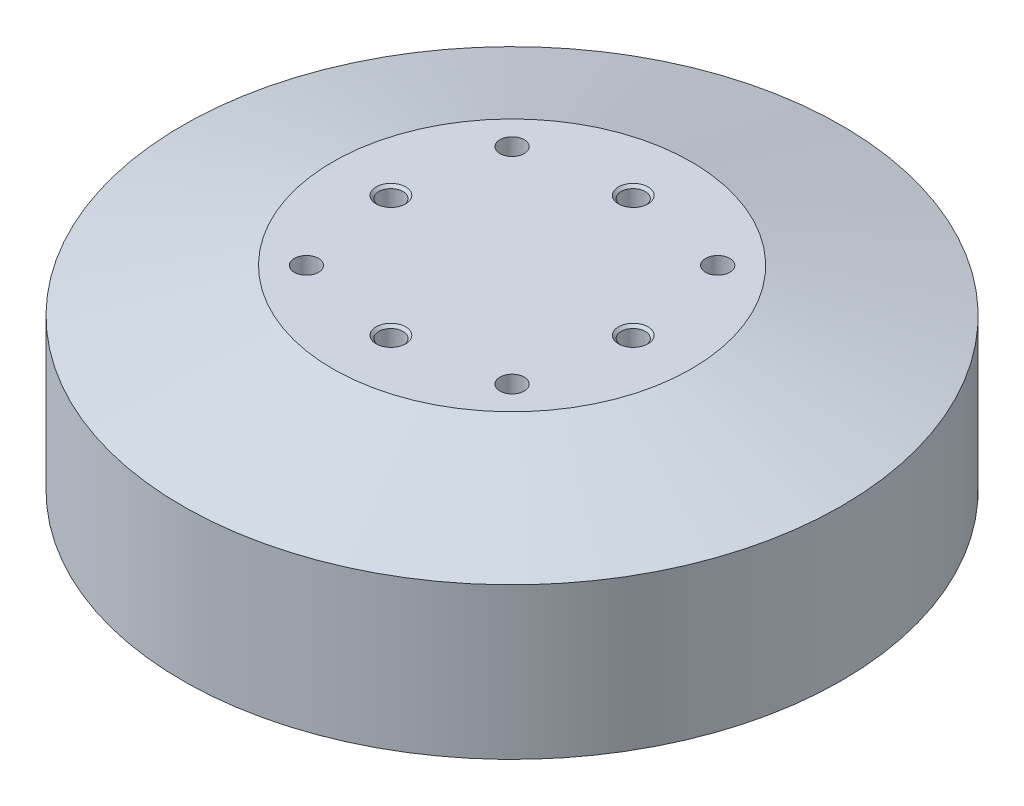
SolidWorks part; units mm, degrees
ref_plane "Front" through (0, 0, 0) normal (0, 0, 1) x (1, 0, 0)
ref_plane "Top" through (0, 0, 0) normal (0, 1, 0) x (1, 0, 0)
ref_plane "Right" through (0, 0, 0) normal (1, 0, 0) x (0, 0, -1)
sketch "Sketch3" plane through (0, 0, 0) normal (0, 0, 1) x (1, 0, 0)
  line L0 (0, -10.05) -> (0, 10.05)
  line L1 (0, 10.05) -> (18.5, 10.05)
  line L2 (18.5, 10.05) -> (34, 5.55)
  line L3 (34, 5.55) -> (34, -10.05)
  line L4 (34, -10.05) -> (0, -10.05)
  point P4 (0, 0)
  dimension "D1" = 18.5
  dimension "D2" = 4.5
  dimension "D3" = 34
  dimension "D4" = 20.1
revolve "Revolve1" add sketch "Sketch3" angle 360 about L0
sketch "Sketch4" plane through (0, -10.05, 0) normal (0, -1, 0) x (1, 0, 0)
  circle A0 centre (0, 0) radius 33
  circle A1 centre (0, 0) radius 34 construction
  dimension "D1" = 1
extrude "Cut-Extrude1" cut sketch "Sketch4" against normal blind 2
sketch "Sketch6" plane through (0, 10.05, 0) normal (0, 1, 0) x (1, 0, 0)
  line L0 (-10.6066, -10.6066) -> (10.6066, 10.6066) construction
  line L5 (10.6066, -10.6066) -> (-10.6066, 10.6066) construction
  line L6 (0, 0) -> (0, 15) construction
  circle A0 centre (0, 0) radius 15 construction
  point P4 (0, 0)
  point P9 (0, 0)
  dimension "D1" = 30
  dimension "D2" = 45
hole_wizard "M3x0.5 Tapped Hole1" positions "Sketch7" profile "Sketch8" tap size "M3x0.5" standard "ANSI Metric"
sketch "Sketch7" plane through (0, 10.05, 0) normal (0, 1, 0) x (1, 0, 0)
  point P0 (-10.6066, 10.6066)
  point P3 (10.6066, 10.6066)
  point P6 (10.6066, -10.6066)
  point P9 (-10.6066, -10.6066)
sketch "Sketch8" plane through (-10.6066, 10.05, -10.6066) normal (1, 0, 0) x (0, 0, 1)
  line L0 (0, 0) -> (0, 8.2511)
  line L1 (0, 8.2511) -> (1.25, 7.5)
  line L2 (1.25, 7.5) -> (1.25, 0)
  line L5 (1.25, 0) -> (0, 0)
  line L10 (0, 8.2511) -> (-1.25, 7.5) construction
  line L11 (0, -6.35) -> (0, 107.95) construction
  dimension "Tap Drill Dia." = 2.5
  dimension "Tap Drill Depth" = 7.5
  dimension "Drill Angle" = 118
cosmetic thread "Hole Thread1" parameters "D1"=6, "D2"=3
cosmetic thread "Hole Thread2" parameters "D1"=6, "D2"=3
cosmetic thread "Hole Thread3" parameters "D1"=6, "D2"=3
cosmetic thread "Hole Thread4" parameters "D1"=6, "D2"=3
sketch "Sketch9" plane through (0, 10.05, 0) normal (0, 1, 0) x (1, 0, 0)
  circle A0 centre (0, 0) radius 12.5 construction
  point P3 (0, 12.5)
  point P4 (0, -12.5)
  point P5 (12.5, 0)
  point P6 (-12.5, 0)
  dimension "D1" = 25
hole_wizard "M3x0.5 Tapped Hole2" positions "Sketch10" profile "Sketch11" tap size "M3x0.5" standard "ANSI Metric"
sketch "Sketch10" plane through (0, 10.05, 0) normal (0, 1, 0) x (1, 0, 0)
  point P0 (0, 12.5)
  point P3 (0, -12.5)
  point P6 (-12.5, 0)
  point P9 (12.5, 0)
sketch "Sketch11" plane through (0, 10.05, -12.5) normal (1, 0, 0) x (0, 0, 1)
  line L0 (0, 0) -> (0, 8.2511)
  line L1 (0, 8.2511) -> (1.25, 7.5)
  line L2 (1.25, 7.5) -> (1.25, 0.275)
  line L3 (1.25, 0.275) -> (1.525, 0)
  line L5 (1.525, 0) -> (0, 0)
  line L6 (-1.25, 0.275) -> (-1.525, 0) construction
  line L10 (0, 8.2511) -> (-1.25, 7.5) construction
  line L11 (0, -6.35) -> (0, 107.95) construction
  dimension "Tap Drill Dia." = 2.5
  dimension "Tap Drill Depth" = 7.5
  dimension "Near C'Sink Dia." = 3.05
  dimension "Near C'Sink Angle" = 90
  dimension "Drill Angle" = 118
cosmetic thread "Hole Thread5" parameters "D1"=6, "D2"=3
cosmetic thread "Hole Thread6" parameters "D1"=6, "D2"=3
cosmetic thread "Hole Thread7" parameters "D1"=6, "D2"=3
cosmetic thread "Hole Thread8" parameters "D1"=6, "D2"=3
